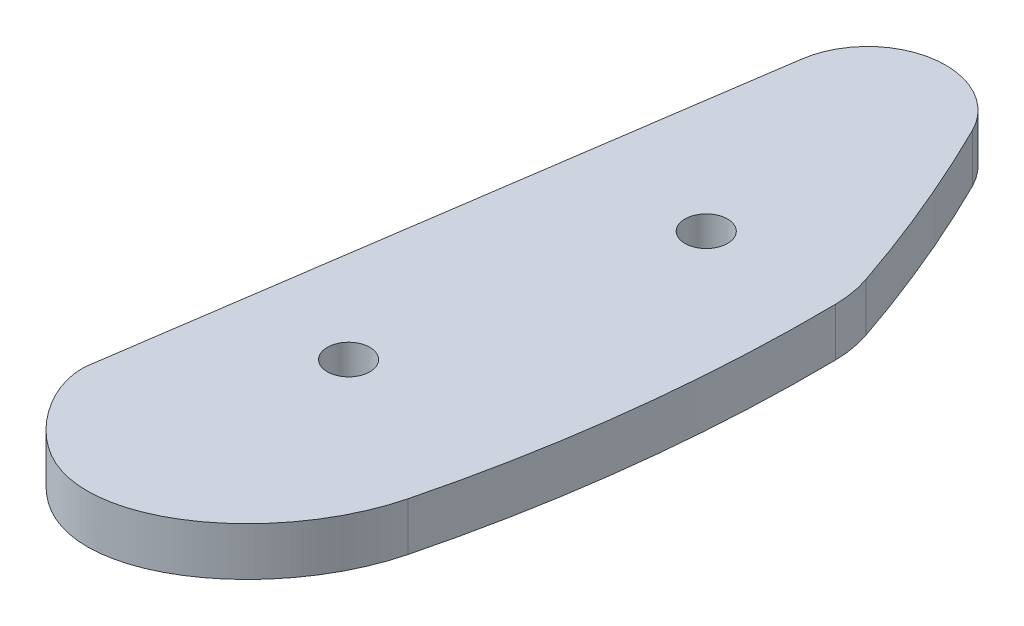
SolidWorks part; units mm, degrees
ref_plane "Front Plane" through (0, 0, 0) normal (0, 0, 1) x (1, 0, 0)
ref_plane "Top Plane" through (0, 0, 0) normal (0, 1, 0) x (1, 0, 0)
ref_plane "Right Plane" through (0, 0, 0) normal (1, 0, 0) x (0, 0, -1)
sketch "Sketch1" plane through (0, 0, 0) normal (0, 1, 0) x (1, 0, 0)
  line L44 (-41.4826, 160.3656) -> (-50.9327, 96.0562)
  arc A149 (-22.4566, 100.5997) -> (-17.768, 140.1479) centre (-171.2572, 138.2924) ccw
  arc A150 (-17.768, 140.1479) -> (-18.4178, 143.9365) centre (-30, 140) ccw
  arc A151 (-18.4178, 143.9365) -> (-26.2563, 162.7822) centre (-163.7532, 94.5401) ccw
  arc A152 (-26.2563, 162.7822) -> (-41.4826, 160.3656) centre (-33.4913, 159.1913) ccw
  arc A153 (-50.9327, 96.0562) -> (-50.9791, 95.5373) centre (0.0072, 91.2427) ccw
  spline S0 degree 3 poles (-22.4566, 100.5997) (-25.1765, 89.8622) (-41.6352, 77.5168) (-51.4058, 92.8366) (-50.9327, 96.0562) knots 0 0 0 0 0.694818 1 1 1 1
  dimension "D3" = 65
extrude "Boss-Extrude2" add sketch "Sketch1" along normal blind 5 contours S0 A149 A150 A151 A152 L44 A153
sketch "Sketch2" plane through (0, 5, 0) normal (0, 1, 0) x (1, 0, 0)
  circle A0 centre (-31, 140) radius 2.2
  circle A1 centre (-38, 110) radius 2.2
  dimension "D1" = 4.4
  dimension "D2" = 4.4
extrude "Cut-Extrude1" cut sketch "Sketch2" against normal up to next
